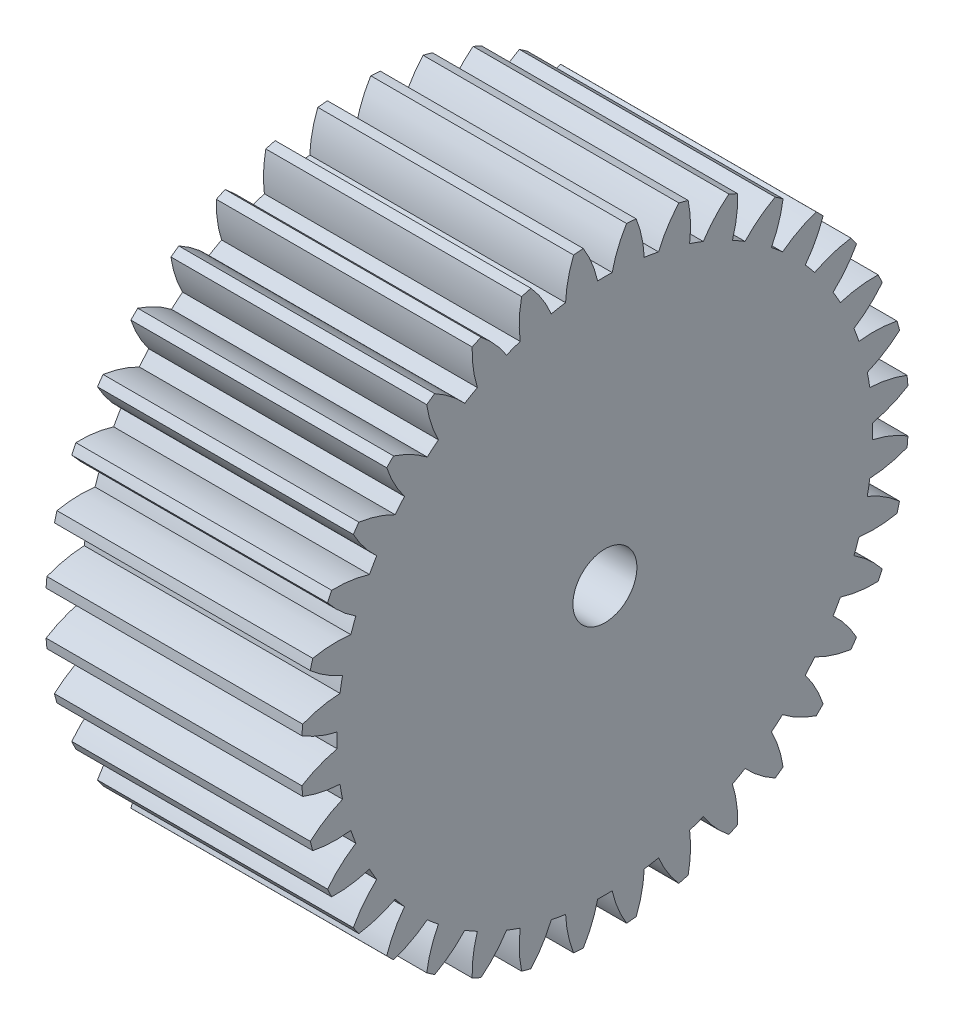
SolidWorks part; units mm, degrees
ref_plane "Plane1" through (0, 0, 0) normal (0, 0, 1) x (1, 0, 0)
ref_plane "Plane2" through (0, 0, 0) normal (0, 1, 0) x (1, 0, 0)
ref_plane "Plane3" through (0, 0, 0) normal (1, 0, 0) x (0, 0, -1)
other "Configuration Table"
sketch "HoldingSke" plane through (0, 0, 0) normal (0, 1, 0) x (1, 0, 0)
  line L0 (0, 0) -> (0.809, -0.5878)
  line L1 (-15, 0) -> (100, 0) construction
  line L2 (0, 0) -> (-2.1039, 2.3779)
  line L3 (0, 0) -> (-11.863, 4.5341)
  line L4 (0, 0) -> (6.9867, 5.0761)
  line L5 (0, 0) -> (-46.8476, -17.4728)
  line L6 (0, 0) -> (-13.2634, -8.9489)
  line L7 (-2.1039, 2.3779) -> (8.6586, 51.2059)
  line L8 (-76.2, 54.61) -> (-75.5, 54.61)
  line L9 (-71.009, 38.7566) -> (-53.1078, 45.2721)
  line L10 (-76.2, 71.12) -> (104.1128, 71.12)
  line L11 (0, 0) -> (-16, 0)
  line L12 (-76.2, 101.6) -> (-76.162, 101.6)
  line L13 (24.9733, 27.94) -> (52.9518, 28.4284)
  line L14 (24.9733, 27.94) -> (24.9743, 27.94)
  line L15 (24.9733, 27.94) -> (100.4006, 29.5858)
  line L16 (-63.627, -1) -> (-12.827, -1)
  circle A0 centre (0, 0) radius 2
  circle A1 centre (0, 0) radius 16.749
  circle A2 centre (0, 0) radius 37.5
  circle A3 centre (0, 0) radius 2
  dimension "MHD" = 33.498
  dimension "Hub_dia" = 75
  dimension "Bore" = 4
  dimension "MBD" = 4
  dimension "Num_teeth" = 36
  dimension "Pitch" = 1
  dimension "Overall_len" = 50
  dimension "Show_teeth" = 36
  dimension "Thickness" = 16
  dimension "OAL" = 50.0001
  dimension "T_dim" = 0.7
  dimension "Ap" = 20
  dimension "H" = 19.05
  dimension "Pitch_radius" = 180.3128
  dimension "Width" = 16
  dimension "Backlash" = 0.038
  dimension "Addendum_fac" = 1
  dimension "Dedendum_fac" = 1.25
  dimension "Clearance_fac" = 0.25
  dimension "Dedendum_add" = 0.001
  dimension "Module" = 1
sketch "BasProSke" plane through (0, 0, 0) normal (0, 1, 0) x (1, 0, 0)
  line L0 (-10, 0) -> (60, 0) construction
  line L1 (0, 0) -> (0, 19)
  line L2 (0, 0) -> (16, 0)
  line L3 (16, 0) -> (16, 19)
  line L4 (16, 19) -> (0, 19)
  dimension "Thickness" = 16
  dimension "Diameter" = 38
revolve "Base-Revolve" add sketch "BasProSke" angle 360 about L0
sketch "TooCutSke" plane through (0, 0, 0) normal (1, 0, 0) x (0, 0, -1)
  line L1 (0, 0) -> (0, 107) construction
  line L2 (0, 0) -> (-0.8516, 17.9798) construction
  line L3 (0, 0) -> (-3.1351, 35.8344) construction
  line L4 (-0.8516, 17.9798) -> (-1.5676, 17.9172) construction
  arc A0 (0.4547, 16.7428) -> (-0.4547, 16.7428) centre (0, 0) ccw
  arc A1 (1.3689, 18.9761) -> (-1.3689, 18.9761) centre (0, 0) ccw
  circle A2 centre (0, 0) radius 18 construction
  circle A3 centre (0, 0) radius 16.9145 construction
  arc A4 (-0.4547, 16.7428) -> (-1.3689, 18.9761) centre (-7.4808, 15.1702) ccw
  arc A5 (1.3689, 18.9761) -> (0.4547, 16.7428) centre (7.4808, 15.1702) ccw
  dimension "Root_dia" = 33.498
  dimension "Overcut_dia" = 38.0508
  dimension "Pitch_dia" = 36
  dimension "Base_dia" = 33.8289
  dimension "Flank_rad" = 7.2
  dimension "Half_ang" = 5
  dimension "Half_CT" = 0.7186
extrude "ToothCut" cut sketch "TooCutSke" along normal through all
fillet "Breaks" [suppressed] radius 0.02
fillet "RootFillets" [suppressed] radius 0.251
pattern_circular "TeethCuts" count 36 every 10 about axis through (-10, 0, 0) along (1, 0, 0) of "ToothCut", "RootFillets", "Breaks"
sketch "HubNeaOneSke" plane through (0, 0, 0) normal (-1, 0, 0) x (0, 0, 1)
  circle A0 centre (0, 0) radius 16.749
  dimension "Diameter" = 33.498
extrude "HubNearOne" [suppressed] add sketch "HubNeaOneSke" along normal blind 34.0001
sketch "HubNeaBotSke" plane through (0, 0, 0) normal (-1, 0, 0) x (0, 0, 1)
  circle A0 centre (0, 0) radius 16.749
  dimension "Diameter" = 33.498
extrude "HubNearBoth" [suppressed] add sketch "HubNeaBotSke" along normal blind 17
ref_plane "FarPln" through (16, 0, 0) normal (1, 0, 0) x (0, 0, -1)
sketch "HubFarSke" plane through (16, 0, 0) normal (1, 0, 0) x (0, 0, -1)
  circle A0 centre (0, 0) radius 16.749
  dimension "Diameter" = 33.498
extrude "HubFar" [suppressed] add sketch "HubFarSke" along normal blind 17
sketch "BorSke" plane through (0, 0, 0) normal (1, 0, 0) x (0, 0, -1)
  circle A0 centre (0, 0) radius 2
  dimension "Diameter" = 4
extrude "Bore" cut sketch "BorSke" along normal mid plane 100.0001
sketch "KeySke" plane through (0, 0, 0) normal (1, 0, 0) x (0, 0, -1)
  line L0 (-0.8, 0) -> (-0.8, 2.7)
  line L1 (-0.8, 2.7) -> (0.8, 2.7)
  line L2 (0.8, 2.7) -> (0.8, 0)
  line L3 (0, 0) -> (0, 34) construction
  line L4 (-0.8, 0) -> (0.8, 0)
  dimension "Offset" = 2.7
extrude "Keyway" [suppressed] cut sketch "KeySke" along normal mid plane 100.0001
pattern_circular "Keyway2" [suppressed] count 2 every 90 about axis through (-10, 0, 0) along (1, 0, 0)
equation "' \"Module@HoldingSke\" = 6.35"
equation "' \"Num_teeth@HoldingSke\" = 12"
equation "' \"Ap@HoldingSke\" =  20"
equation "' \"Ap@HoldingSke\" = 20"
equation "' \"Width@HoldingSke\" = 0.5 * 25.4"
equation "' \"Hub_dia@HoldingSke\"= 1 * 25.4"
equation "' \"Hub_dia@HoldingSke\" = 1 * 25.4"
equation "' \"Overall_len@HoldingSke\" = 1.0 * 25.4"
equation "' \"Bore@HoldingSke\" = 0.75 * 25.4"
equation "' \"T_dim@HoldingSke\" = 0.1 * 25.4"
equation "' \"Width@KeySke\" = 0.25 * 25.4"
equation "' \"Show_teeth@HoldingSke\" = 13"
equation "' \"Backlash@HoldingSke\" = 0.009 * 25.4"
equation "' \"Addendum_fac@HoldingSke\" = 1.0"
equation "' \"Dedendum_fac@HoldingSke\" = 1.25"
equation "' \"Dedendum_add@HoldingSke\" = 0.00005 * 25.4"
equation "' \"Clearance_fac@HoldingSke\" = 0.25"
equation "\"Pitch@HoldingSke\" = 1 / \"Module@HoldingSke\""
equation "\"Overcut_dia@TooCutSke\" = (\"Num_teeth@HoldingSke\" + 2 * \"Addendum_fac@HoldingSke\") / \"Pitch@HoldingSke\" + 0.002 * 25.4"
equation "\"Pitch_dia@TooCutSke\" = \"Num_teeth@HoldingSke\" / \"Pitch@HoldingSke\""
equation "\"Base_dia@TooCutSke\" = \"Num_teeth@HoldingSke\" / \"Pitch@HoldingSke\" * cos((\"Ap@HoldingSke\"  * 3.14159265 / 180))"
equation "\"Root_dia@TooCutSke\" = (\"Num_teeth@HoldingSke\" + 2) / \"Pitch@HoldingSke\" - 2 * (\"Addendum_fac@HoldingSke\" + \"Dedendum_fac@HoldingSke\") / \"Pitch@HoldingSke\" - \"Dedendum_add@HoldingSke\" * 2"
equation "\"Half_ang@TooCutSke\" = 180 / \"Num_teeth@HoldingSke\""
equation "\"Half_CT@TooCutSke\" = \"Num_teeth@HoldingSke\" / \"Pitch@HoldingSke\" * sin((3.14159265 / 2 / \"Num_teeth@HoldingSke\")) / 2 - 7 * \"Backlash@HoldingSke\" / 4"
equation "\"Flank_rad@TooCutSke\" = \"Num_teeth@HoldingSke\" / \"Pitch@HoldingSke\" / 5"
equation "\"Radius@RootFillets\" = \"Clearance_fac@HoldingSke\" / \"Pitch@HoldingSke\" + \"Dedendum_add@HoldingSke\""
equation "\"Break_rad@Breaks\" = 0.02 / \"Pitch@HoldingSke\""
equation "\"Thickness@HoldingSke\" = \"Width@HoldingSke\""
equation "\"OAL@HoldingSke\" = \"Thickness@HoldingSke\""
equation "\"MHD@HoldingSke\" = (\"Num_teeth@HoldingSke\" + 2) / \"Pitch@HoldingSke\" - 2 * (\"Addendum_fac@HoldingSke\" + \"Dedendum_fac@HoldingSke\")  / \"Pitch@HoldingSke\" - \"Dedendum_add@HoldingSke\" * 2"
equation "\"MBD@HoldingSke\" = (\"Num_teeth@HoldingSke\" + 2) / \"Pitch@HoldingSke\" - 2 * (\"Addendum_fac@HoldingSke\" + \"Dedendum_fac@HoldingSke\")  / \"Pitch@HoldingSke\" - \"Dedendum_add@HoldingSke\" * 2 - 0.002 * 25.4"
equation "\"MHD@HoldingSke\" = ((sgn( \"MHD@HoldingSke\" - \"Hub_dia@HoldingSke\" )-1)*( \"MHD@HoldingSke\" - \"Hub_dia@HoldingSke\" ))/-2+ \"Hub_dia@HoldingSke\""
equation "\"MBD@HoldingSke\" = ((sgn( \"MBD@HoldingSke\" - \"Bore@HoldingSke\" )-1)*( \"MBD@HoldingSke\" - \"Bore@HoldingSke\" ))/-2+ \"Bore@HoldingSke\""
equation "\"OAL@HoldingSke\" = ((sgn( \"OAL@HoldingSke\" - \"Overall_len@HoldingSke\" )+1)*( \"OAL@HoldingSke\" - \"Overall_len@HoldingSke\" ))/2 + \"Overall_len@HoldingSke\" + 0.000002 * 25.4"
equation "\"Num_teeth@TeethCuts\" = int( \"Show_teeth@HoldingSke\" ) + 1"
equation "\"Num_teeth@TeethCuts\" = ((sgn( \"Num_teeth@TeethCuts\" - \"Num_teeth@HoldingSke\" )-1)*( \"Num_teeth@TeethCuts\" - \"Num_teeth@HoldingSke\" ))/-2+ \"Num_teeth@HoldingSke\""
equation "\"Num_teeth@TeethCuts\" = ((sgn( \"Num_teeth@TeethCuts\" - 2.0)+1)*( \"Num_teeth@TeethCuts\" - 2.0))/2 +2.0"
equation "\"Angle@TeethCuts\" = 360.0 / \"Num_teeth@HoldingSke\""
equation "\"Diameter@BasProSke\" = (\"Num_teeth@HoldingSke\" + 2 * \"Addendum_fac@HoldingSke\") / \"Pitch@HoldingSke\""
equation "\"Thickness@BasProSke\"  = \"Thickness@HoldingSke\""
equation "' \"Fillet_rad@BasProSke\" =  \"Thickness@HoldingSke\" * 0.05"
equation "' \"Fillet_rad@BasProSke\" = \"Thickness@HoldingSke\" * 0.05"
equation "\"MHD@HoldingSke\" = ((sgn( \"MHD@HoldingSke\" - \"Root_dia@TooCutSke\" )-1)*( \"MHD@HoldingSke\" - \"Root_dia@TooCutSke\" ))/-2+ \"Root_dia@TooCutSke\""
equation "\"Diameter@HubNeaOneSke\" = \"MHD@HoldingSke\""
equation "\"Length@HubNearOne\" = \"OAL@HoldingSke\" - \"Thickness@BasProSke\""
equation "\"Diameter@HubNeaBotSke\" = \"MHD@HoldingSke\""
equation "\"Length@HubNearBoth\" = ( \"OAL@HoldingSke\" - \"Thickness@BasProSke\" ) / 2.0"
equation "\"Thickness@FarPln\" = \"Thickness@BasProSke\""
equation "\"Diameter@HubFarSke\" = \"MHD@HoldingSke\""
equation "\"Length@HubFar\" = ( \"OAL@HoldingSke\" - \"Thickness@BasProSke\" ) / 2.0"
equation "\"Diameter@BorSke\" = \"MBD@HoldingSke\""
equation "\"D1@Bore\" = \"OAL@HoldingSke\" * 2.0"
equation "\"D1@Keyway\" = \"OAL@HoldingSke\" * 2.0"
equation "\"Offset@KeySke\" = \"T_dim@HoldingSke\" + \"MBD@HoldingSke\" / 2.0"
